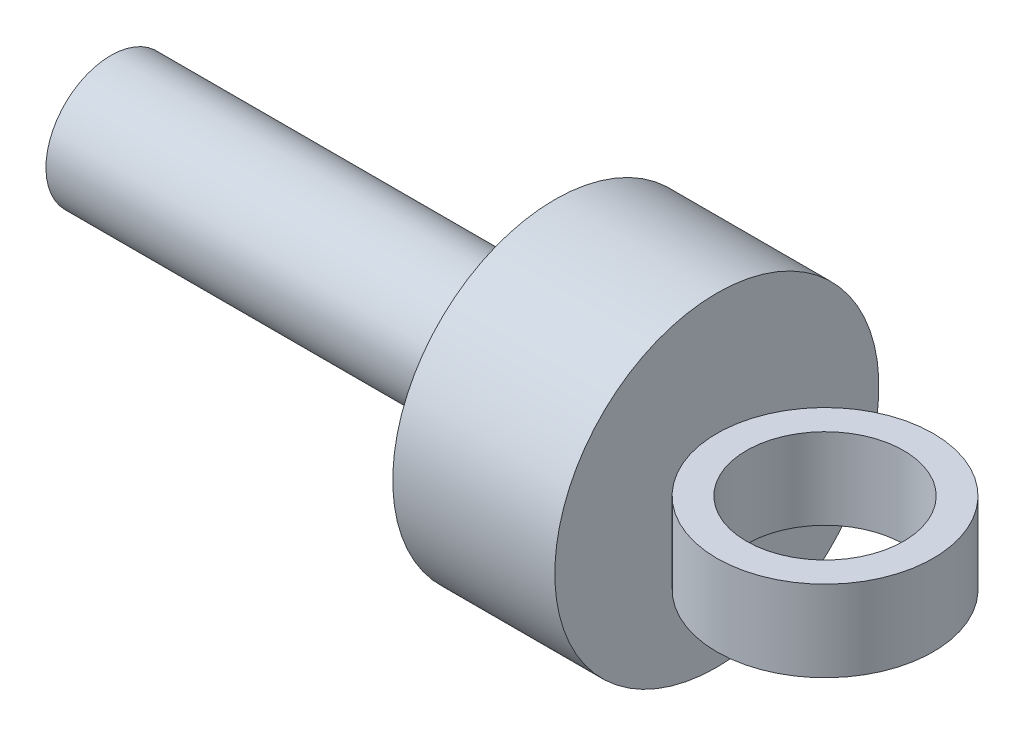
SolidWorks part; units mm, degrees
ref_plane "Front Plane" through (0, 0, 0) normal (0, 0, 1) x (1, 0, 0)
ref_plane "Top Plane" through (0, 0, 0) normal (0, 1, 0) x (1, 0, 0)
ref_plane "Right Plane" through (0, 0, 0) normal (1, 0, 0) x (0, 0, -1)
sketch "Sketch1" plane through (0, 0, 0) normal (0, 0, 1) x (1, 0, 0)
  line L0 (0, 0) -> (-112.2, 0)
  line L1 (-112.2, 0) -> (-112.2, 12)
  line L2 (-112.2, 12) -> (-1, 12)
  line L3 (-1, 12) -> (-1, 29)
  line L4 (-1, 29) -> (-30, 29)
  line L5 (-30, 29) -> (-30, 30)
  line L6 (-30, 30) -> (0, 30)
  line L7 (0, 30) -> (0, 0)
  dimension "D1" = 12
  dimension "D2" = 111.2
  dimension "D3" = 30
  dimension "D4" = 1
  dimension "D5" = 1
  dimension "D6" = 30
revolve "Revolve1" add sketch "Sketch1" angle 360 about L0
sketch "Sketch2" plane through (0, 0, 0) normal (0, 1, 0) x (1, 0, 0)
  line L0 (0, -30) -> (0, 30) construction
  circle A0 centre (20.03, 0) radius 14.555
  circle A1 centre (20.03, 0) radius 20.03
  dimension "D1" = 40.06
  dimension "D2" = 29.11
extrude "Boss-Extrude1" add sketch "Sketch2" along normal mid plane 15 separate body
